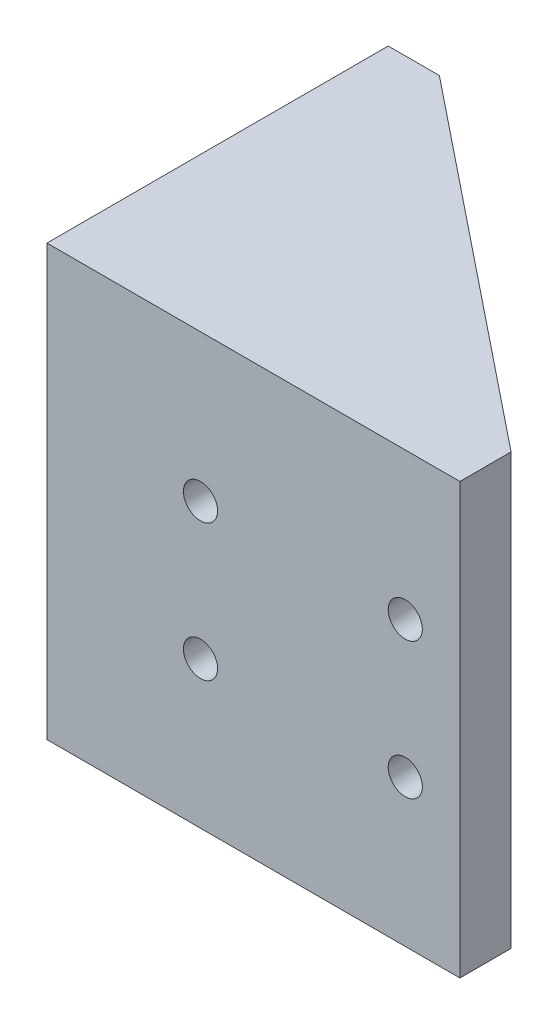
SolidWorks part; units mm, degrees
material "6061 合金"
ref_plane "前视基准面" through (0, 0, 0) normal (0, 0, 1) x (1, 0, 0)
ref_plane "上视基准面" through (0, 0, 0) normal (0, 1, 0) x (1, 0, 0)
ref_plane "右视基准面" through (0, 0, 0) normal (1, 0, 0) x (0, 0, -1)
sketch "草图1" plane through (0, 0, 0) normal (0, 1, 0) x (1, 0, 0)
  line L0 (0, 0) -> (24.2, 0)
  line L1 (24.2, 0) -> (24.2, 3)
  line L2 (24.2, 3) -> (3, 20)
  line L3 (3, 20) -> (0, 20)
  line L4 (0, 20) -> (0, 0)
  dimension "D1" = 24.2
  dimension "D3" = 3
  dimension "D4" = 20
extrude "凸台-拉伸1" add sketch "草图1" along normal mid plane 25.2
sketch "草图2" plane through (0, 0, -20) normal (0, 0, -1) x (-1, 0, 0)
  line L0 (-3, 12.6) -> (-3, -12.6) construction
  line L1 (-3, -10.1) -> (-24.2, -10.1)
  line L2 (-3, -10.1) -> (-3, 10.1)
  line L3 (-3, 10.1) -> (-24.2, 10.1)
  line L4 (-24.2, -10.1) -> (-24.2, 10.1)
  line L5 (-13.6, 10.1) -> (-13.6, -10.1) construction
  line L6 (-3, 0) -> (-24.2, 0) construction
  line L7 (-24.2, 12.6) -> (-24.2, -12.6) construction
  line L8 (-24.2, -12.6) -> (-3, -12.6) construction
  point P268 (-13.6, 0)
  dimension "D1" = 2.5
extrude "切除-拉伸1" cut sketch "草图2" against normal up to vertex (17 mm away) up to point (24.2, 12.6, -3)
sketch "草图3" plane through (0, 0, 0) normal (0, 0, 1) x (1, 0, 0)
  line L0 (0, 0) -> (24.2, 0) construction
  line L1 (0, 12.6) -> (0, -12.6) construction
  line L2 (24.2, 12.6) -> (24.2, -12.6) construction
  line L3 (15, 0) -> (15, -12.6) construction
  line L4 (0, -12.6) -> (24.2, -12.6) construction
  circle A0 centre (21, -4) radius 1
  circle A1 centre (21, 4) radius 1
  circle A2 centre (9, 4) radius 1
  circle A3 centre (9, -4) radius 1
  dimension "D4" = 2
  dimension "D1" = 8
  dimension "D2" = 12
  dimension "D3" = 15
extrude "切除-拉伸2" cut sketch "草图3" against normal through all
sketch "草图4" plane through (3, 0, 0) normal (1, 0, 0) x (0, 0, -1)
  line L0 (0, 0) -> (20, 0) construction
  line L1 (20, -10.1) -> (20, 10.1) construction
  line L2 (0, 12.6) -> (0, -12.6) construction
  circle A0 centre (16, 7) radius 1.6
  circle A1 centre (16, -7) radius 1.6
  dimension "D3" = 3.2
  dimension "D1" = 14
  dimension "D2" = 16
extrude "切除-拉伸3" cut sketch "草图4" against normal through all
fillet "圆角1" radius 5 2 edges at (13.6, -10.1, -3) (13.6, 10.1, -3)
sketch "草图6" plane through (0, 0, -20) normal (0, 0, -1) x (-1, 0, 0)
  line L0 (-3, 5.1) -> (-24.2, 5.1) construction
  line L1 (-24.2, -5.1) -> (-3, -5.1) construction
  line L2 (-3, -5.1) -> (-3, 5.1)
  line L4 (-8, 10.1) -> (-24.2, 10.1)
  line L5 (-24.2, 12.6) -> (-24.2, 5.1) construction
  line L6 (-24.2, 10.1) -> (-24.2, -10.1)
  line L7 (-24.2, -5.1) -> (-24.2, -12.6) construction
  line L8 (-24.2, -10.1) -> (-8, -10.1)
  line L9 (-3, -10.1) -> (-17.9647, -10.1) construction
  line L14 (-3, -10.1) -> (-17.9647, -10.1) construction
  arc A1 (-3, 5.1) -> (-8, 10.1) centre (-8, 5.1) ccw
  arc A2 (-8, -10.1) -> (-3, -5.1) centre (-8, -5.1) ccw
  dimension "D1" = 10
extrude "切除-拉伸4" cut sketch "草图6" against normal up to surface (17 mm away) up to face at (8, -4, -3)
